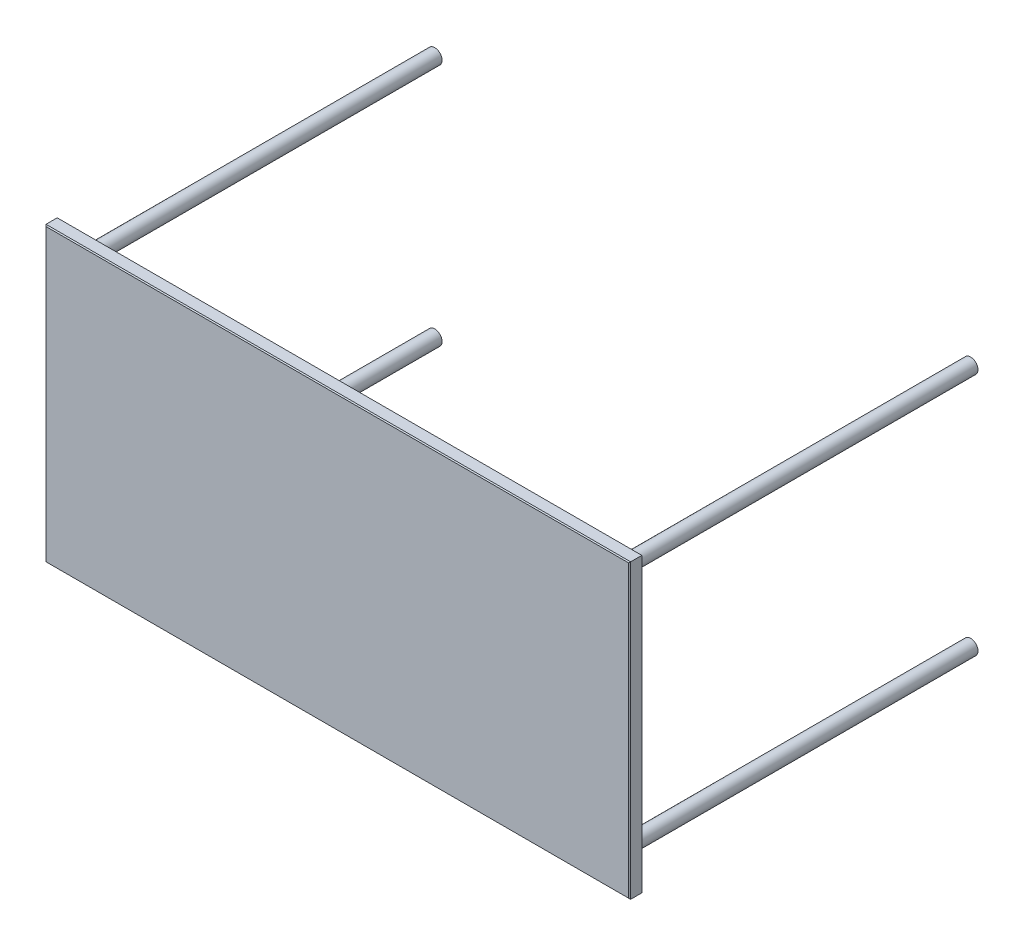
SolidWorks part; units mm, degrees
ref_plane "前视基准面" through (0, 0, 0) normal (0, 0, 1) x (1, 0, 0)
ref_plane "上视基准面" through (0, 0, 0) normal (0, 1, 0) x (1, 0, 0)
ref_plane "右视基准面" through (0, 0, 0) normal (1, 0, 0) x (0, 0, -1)
other "Configuration Table"
sketch "Sketch1" plane through (0, 0, 0) normal (0, 0, 1) x (1, 0, 0)
  line L1 (-600, -300) -> (600, -300)
  line L2 (-600, -300) -> (-600, 300)
  line L3 (-600, 300) -> (600, 300)
  line L4 (600, -300) -> (600, 300)
  line L5 (-600, -300) -> (600, 300) construction
  line L6 (-600, 300) -> (600, -300) construction
  point P0 (0, 0)
extrude "Boss-Extrude1" add sketch "Sketch1" along normal blind 25
sketch "Sketch2" plane through (0, 0, 0) normal (0, 0, 1) x (1, 0, 0)
  circle A0 centre (550, 250) radius 15
  circle A1 centre (-550, 250) radius 15
  circle A2 centre (-550, -250) radius 15
  circle A3 centre (550, -250) radius 15
extrude "Boss-Extrude2" add sketch "Sketch2" against normal blind 725
chamfer "Chamfer1" distance 2 angle 45 4 edges at (0, -300, 25) (-600, 0, 25) (0, 300, 25) (600, 0, 25)
